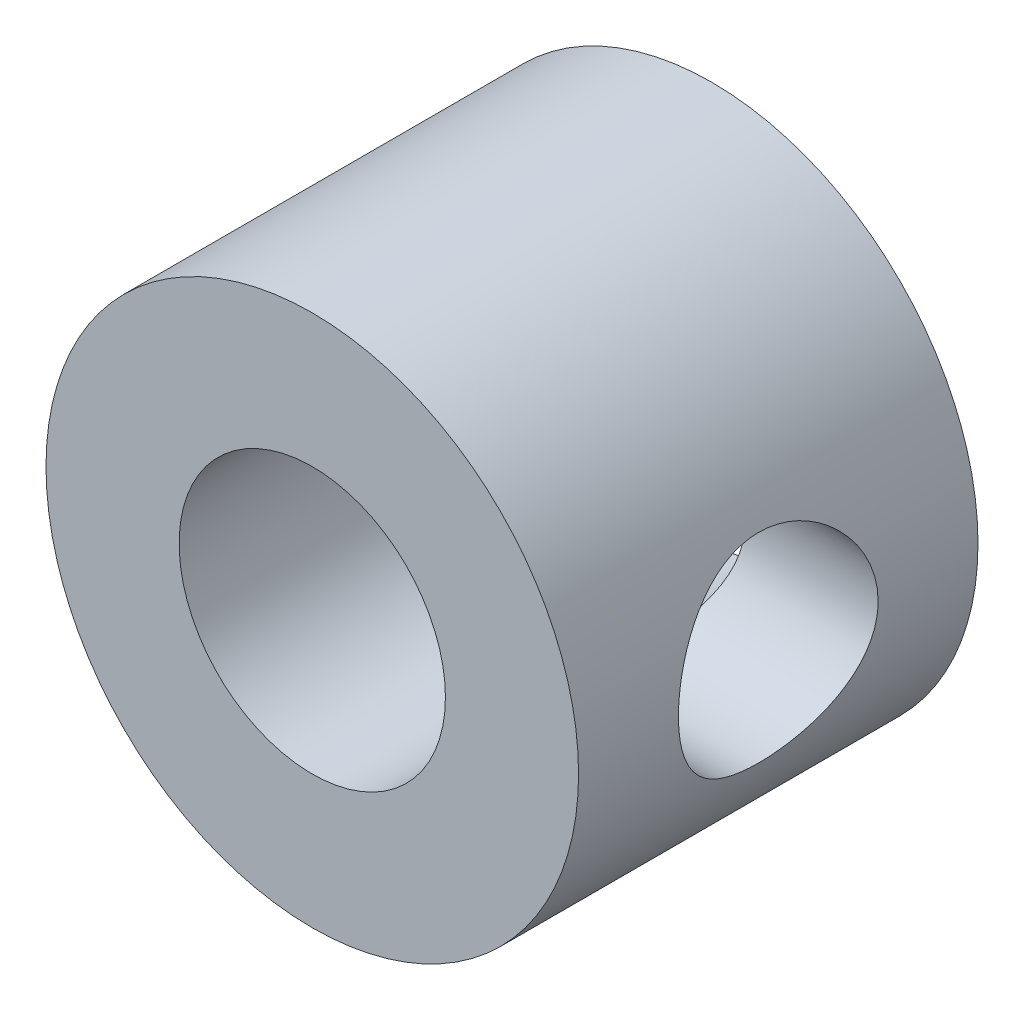
SolidWorks part; units mm, degrees
ref_plane "前视基准面" through (0, 0, 0) normal (0, 0, 1) x (1, 0, 0)
ref_plane "上视基准面" through (0, 0, 0) normal (0, 1, 0) x (1, 0, 0)
ref_plane "右视基准面" through (0, 0, 0) normal (1, 0, 0) x (0, 0, -1)
other "Configuration Table"
sketch "草图1" plane through (0, 0, 0) normal (0, 0, 1) x (1, 0, 0)
  circle A0 centre (0, 0) radius 4
  circle A1 centre (0, 0) radius 2.025
extrude "轴向尺寸_6" add sketch "草图1" along normal blind 6
other "内径改为用户指定D4" face at (2.025, 0, 6) parameters "D1"=0.025
sketch "草图2" plane through (0, 0, 0) normal (1, 0, 0) x (0, 0, -1)
  circle A0 centre (-3, 0) radius 1.5
extrude "径向M3螺纹大径包络" cut sketch "草图2" along normal through all
